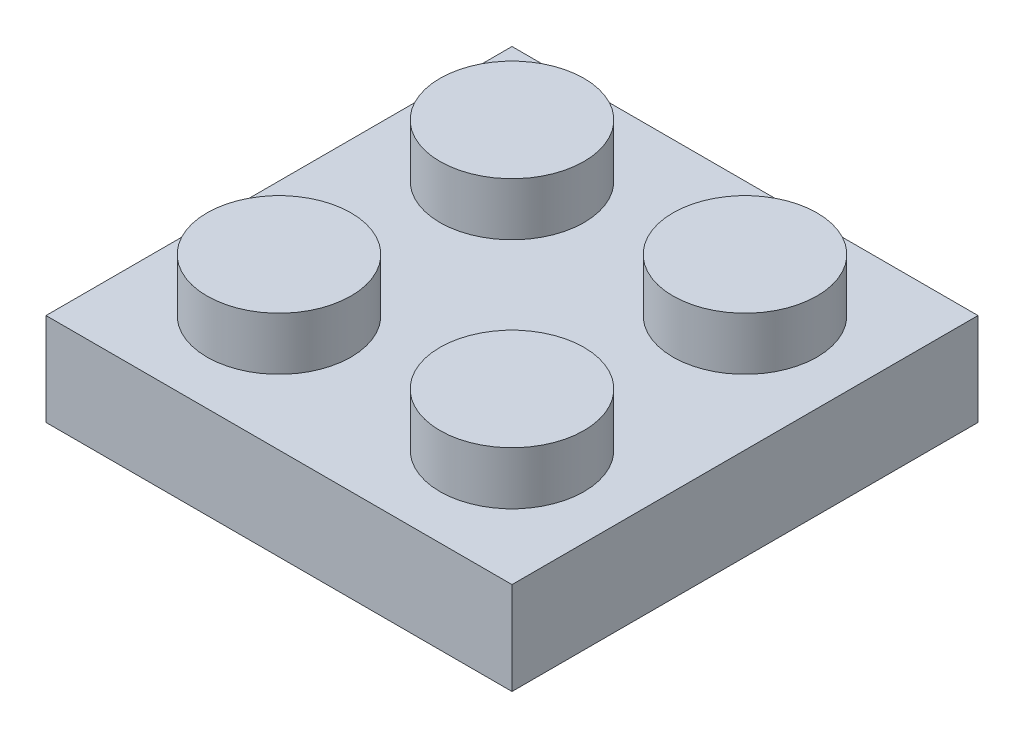
SolidWorks part; units mm, degrees
ref_plane "Front Plane" through (0, 0, 0) normal (0, 0, 1) x (1, 0, 0)
ref_plane "Top Plane" through (0, 0, 0) normal (0, 1, 0) x (1, 0, 0)
ref_plane "Right Plane" through (0, 0, 0) normal (1, 0, 0) x (0, 0, -1)
sketch "Sketch1" plane through (0, 0, 0) normal (0, 1, 0) x (1, 0, 0)
  line L1 (-7.925, 7.925) -> (7.925, 7.925)
  line L2 (-7.925, 7.925) -> (-7.925, -7.925)
  line L3 (-7.925, -7.925) -> (7.925, -7.925)
  line L4 (7.925, 7.925) -> (7.925, -7.925)
  line L5 (-7.925, 7.925) -> (7.925, -7.925) construction
  line L6 (-7.925, -7.925) -> (7.925, 7.925) construction
  point P0 (0, 0)
  dimension "D1" = 15.85
  dimension "D2" = 15.85
extrude "Boss-Extrude1" add sketch "Sketch1" against normal blind 3.15
sketch "Sketch2" plane through (0, 0, 0) normal (0, 1, 0) x (1, 0, 0)
  line L0 (-7.925, 7.925) -> (-7.925, -7.925) construction
  line L1 (7.925, 7.925) -> (-7.925, 7.925) construction
  line L2 (-7.925, -7.925) -> (7.925, -7.925) construction
  line L3 (7.925, -7.925) -> (7.925, 7.925) construction
  circle A0 centre (-3.9625, 3.9625) radius 2.45
  circle A1 centre (-3.9625, -3.9625) radius 2.45
  circle A2 centre (3.9625, 3.9625) radius 2.45
  circle A3 centre (3.9625, -3.9625) radius 2.45
  dimension "D5" = 3.9625
  dimension "D6" = 3.9625
  dimension "D7" = 3.9625
  dimension "D8" = 3.9625
  dimension "D9" = 4.9
  dimension "D1" = 3.9625
  dimension "D2" = 3.9625
  dimension "D3" = 3.9625
  dimension "D4" = 3.9625
extrude "Boss-Extrude2" add sketch "Sketch2" along normal blind 1.8
shell "Shell1" thickness 1.5
sketch "Sketch3" plane through (0, -1.5, 0) normal (0, -1, 0) x (1, 0, 0)
  circle A0 centre (0, 0) radius 3.25
  circle A1 centre (0, 0) radius 2.45
  dimension "D1" = 6.5
  dimension "D2" = 4.9
extrude "Boss-Extrude3" add sketch "Sketch3" along normal offset from surface (1.45 mm away) 0.2 up to face at (0, -3.15, 0)
